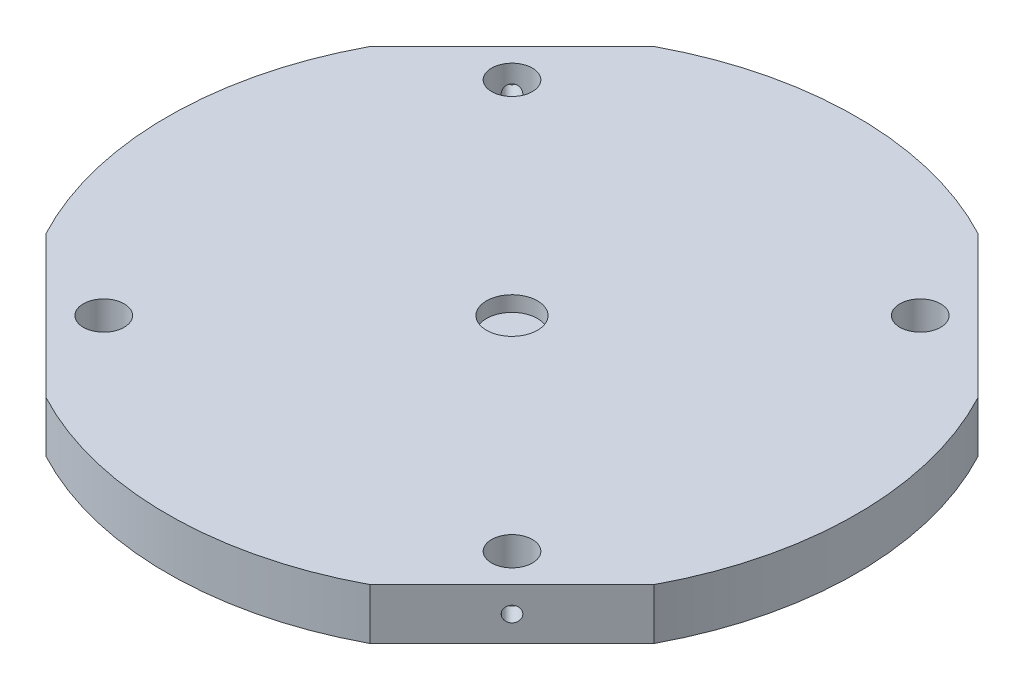
SolidWorks part; units mm, degrees
ref_plane "Front Plane" through (0, 0, 0) normal (0, 0, 1) x (1, 0, 0)
ref_plane "Top Plane" through (0, 0, 0) normal (0, 1, 0) x (1, 0, 0)
ref_plane "Right Plane" through (0, 0, 0) normal (1, 0, 0) x (0, 0, -1)
sketch "Sketch1" plane through (0, 0, 0) normal (0, 1, 0) x (1, 0, 0)
  circle A0 centre (0, 0) radius 67.5
  dimension "D1" = 135
extrude "Boss-Extrude1" add sketch "Sketch1" along normal blind 10
hole_wizard "Ø6.0mm Dowel Hole1" positions "Sketch2" profile "Sketch3" hole size "Ø6.0" standard "ANSI Metric"
sketch "Sketch2" plane through (0, 10, 0) normal (0, 1, 0) x (1, 0, 0)
  line L0 (0, 0) -> (0, 55) construction
  line L2 (0, 0) -> (47.6314, -27.5) construction
  point P0 (0, 55)
  point P14 (47.6314, -27.5)
  point P15 (-47.6314, -27.5)
  dimension "D1" = 55
  dimension "D3" = 55
  dimension "D4" = 120
  dimension "D2" = 3
sketch "Sketch3" plane through (0, 10, -55) normal (1, 0, 0) x (0, 0, 1)
  line L0 (0, 0) -> (0, 10)
  line L1 (0, 10) -> (3, 10)
  line L2 (3, 10) -> (3, 0)
  line L5 (3, 0) -> (0, 0)
  line L11 (0, -6.35) -> (0, 107.95) construction
  dimension "Thru Hole Dia." = 6
  dimension "Thru Hole Depth" = 10
sketch "Sketch4" plane through (0, 10, 0) normal (0, 1, 0) x (1, 0, 0)
  line L0 (0, 67.5) -> (0, -67.5) construction
  line L1 (-67.5, 0) -> (67.5, 0) construction
  circle A0 centre (0, 0) radius 67.5 construction
  circle A1 centre (-40, 40) radius 4
  circle A2 centre (40, 40) radius 4
  circle A3 centre (40, -40) radius 4
  circle A4 centre (-40, -40) radius 4
  point P7 (0, 0)
  point P12 (0, 0)
  dimension "D3" = 8
  dimension "D1" = 40
  dimension "D2" = 40
extrude "Cut-Extrude1" cut sketch "Sketch4" against normal through all and the other way through all
sketch "Sketch5" plane through (0, 10, 0) normal (0, 1, 0) x (1, 0, 0)
  line L0 (-44.5962, 41.0607) -> (-41.0607, 44.5962) construction
  line L1 (-42.8284, 42.8284) -> (0, 0) construction
  line L2 (0, 67.5) -> (0, -67.5) construction
  line L3 (-31.7437, 59.57) -> (-59.57, 31.7437)
  line L4 (59.57, 31.7437) -> (31.7437, 59.57)
  line L5 (31.7437, -59.57) -> (59.57, -31.7437)
  line L6 (-59.57, -31.7437) -> (-31.7437, -59.57)
  line L7 (0, 0) -> (-45.6569, -45.6569) construction
  circle A0 centre (0, 0) radius 67.5 construction
  circle A1 centre (-40, 40) radius 4 construction
  point P5 (-42.8284, 42.8284)
  point P14 (0, 0)
  point P15 (-45.6569, 45.6569)
  dimension "D1" = 5
  dimension "D2" = 45
  dimension "D3" = 4
  dimension "D4" = 4
extrude "Cut-Extrude-Thin1" cut sketch "Sketch5" against normal through all thin
hole_wizard "Ø3.0mm Dowel Hole1" positions "Sketch6" profile "Sketch7" hole size "Ø3.0" standard "ANSI Metric"
sketch "Sketch6" plane through (45.6569, 0, 45.6569) normal (0.7071, 0, 0.7071) x (0.7071, 0, -0.7071)
  line L0 (0, 0) -> (0, 10) construction
  line L1 (-19.6762, 0) -> (19.6762, 0) construction
  line L2 (-19.6762, 10) -> (19.6762, 10) construction
  point P0 (0, 5)
sketch "Sketch7" plane through (45.6569, 5, 45.6569) normal (0, 1, 0) x (0.7071, 0, -0.7071)
  line L0 (0, 0) -> (0, 4)
  line L1 (0, 4) -> (1.5, 4)
  line L2 (1.5, 4) -> (1.5, 0)
  line L5 (1.5, 0) -> (0, 0)
  line L11 (0, -6.35) -> (0, 107.95) construction
  dimension "Thru Hole Dia." = 3
  dimension "Thru Hole Depth" = 4
pattern_circular "CirPattern1" count 4 over 360 about axis through (0, 10, 0) along (0, -1, 0) of "Ø3.0mm Dowel Hole1"
sketch "Sketch8" plane through (0, 10, 0) normal (0, 1, 0) x (1, 0, 0)
  circle A0 centre (0, 0) radius 5
  dimension "D1" = 10
extrude "Cut-Extrude2" cut sketch "Sketch8" against normal blind 3 and the other way through all
equation "\"Plate Thickness\"= 10mm"
equation "\"Plate Diameter\"= 135mm"
equation "\"D1@Sketch1\"=\"Plate Diameter\""
equation "\"D1@Boss-Extrude1\"=\"Plate Thickness\""
